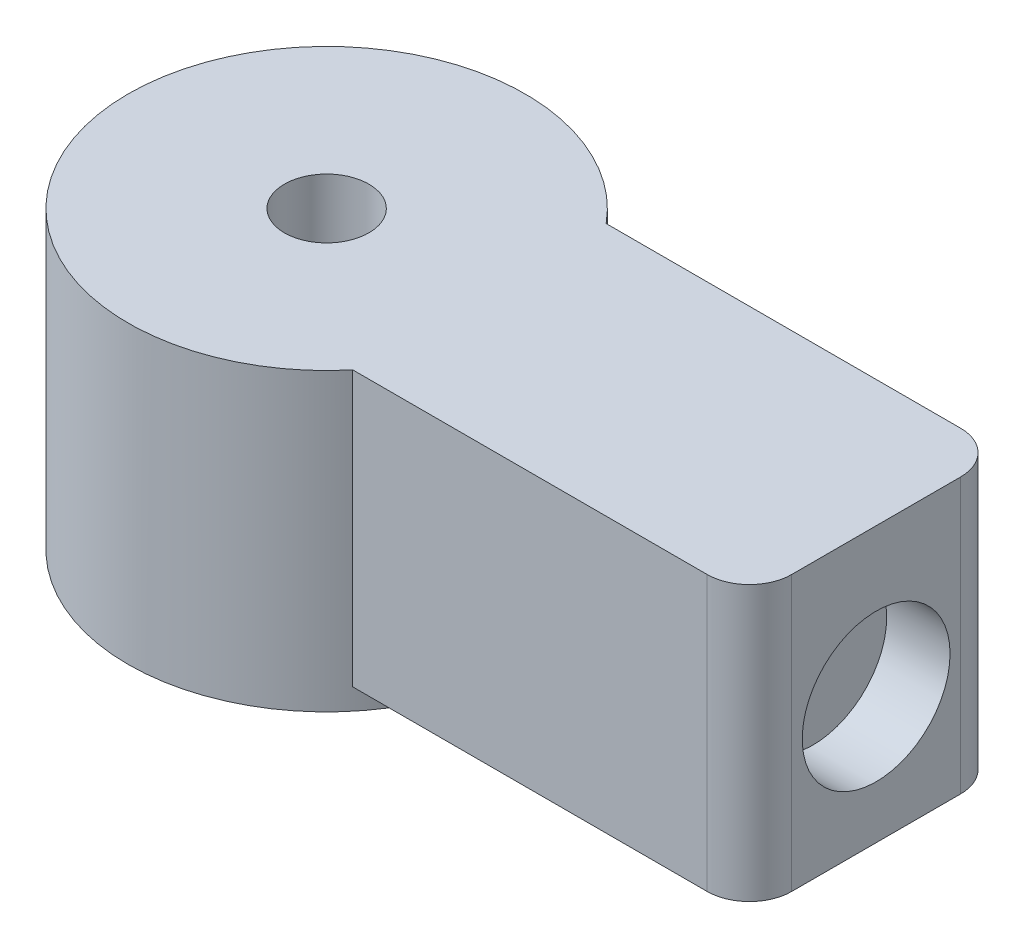
SolidWorks part; units mm, degrees
ref_plane "Front Plane" through (0, 0, 0) normal (0, 0, 1) x (1, 0, 0)
ref_plane "Top Plane" through (0, 0, 0) normal (0, 1, 0) x (1, 0, 0)
ref_plane "Right Plane" through (0, 0, 0) normal (1, 0, 0) x (0, 0, -1)
sketch "Sketch1" plane through (0, 0, 0) normal (0, 1, 0) x (1, 0, 0)
  circle A0 centre (0, 0) radius 2.5
  circle A1 centre (0, 0) radius 4.7
  dimension "D1" = 5
  dimension "D2" = 2.2
extrude "Boss-Extrude1" add sketch "Sketch1" along normal blind 2.5
sketch "Sketch2" plane through (0, 2.5, 0) normal (0, 1, 0) x (1, 0, 0)
  circle A0 centre (0, 0) radius 4.7
  circle A1 centre (0, 0) radius 4.7 construction
  dimension "D1" = 0
extrude "Boss-Extrude2" add sketch "Sketch2" along normal blind 4.5
sketch "Sketch3" plane through (0, 7, 0) normal (0, 1, 0) x (1, 0, 0)
  circle A0 centre (0, 0) radius 1
  dimension "D1" = 2
extrude "Cut-Extrude1" cut sketch "Sketch3" against normal blind 4.5
ref_plane "Plane1" through (4.7, 0, 0) normal (1, 0, 0) x (0, 0, -1)
sketch "Sketch6" plane through (4.7, 0, 0) normal (1, 0, 0) x (0, 0, -1)
  line L1 (3, 6.5) -> (-3, 6.5)
  line L2 (3, 6.5) -> (3, 0.5)
  line L3 (3, 0.5) -> (-3, 0.5)
  line L4 (-3, 6.5) -> (-3, 0.5)
  line L6 (-2.5, 0) -> (2.5, 0) construction
  line L7 (4.7, 7) -> (-4.7, 7) construction
  line L8 (4.7, 0) -> (4.7, 7) construction
  line L9 (-4.7, 7) -> (-4.7, 0) construction
  dimension "D1" = 6
  dimension "D2" = 6
  dimension "D3" = 1.7
  dimension "D4" = 1.7
  dimension "D5" = 0.5
  dimension "D6" = 0.5
extrude "Boss-Extrude3" add sketch "Sketch6" along normal blind 8.31 separate body
sketch "Sketch7" plane through (4.7, 0, 0) normal (-1, 0, 0) x (0, 0, 1)
  line L4 (-3, 6.5) -> (-3, 0.5)
  line L5 (-3, 0.5) -> (3, 0.5)
  line L6 (3, 0.5) -> (3, 6.5)
  line L7 (3, 6.5) -> (-3, 6.5)
  line L8 (-3, 6.5) -> (-3, 0.5)
  line L9 (-3, 0.5) -> (3, 0.5)
  line L10 (3, 0.5) -> (3, 6.5)
  line L11 (3, 6.5) -> (-3, 6.5)
  dimension "D1" = 0
extrude "Boss-Extrude4" add sketch "Sketch7" along normal blind 2
fillet "Fillet1" radius 1 2 edges at (13.01, 3.5, -3) (13.01, 3.5, 3)
sketch "Sketch8" plane through (13.01, 0, 0) normal (1, 0, 0) x (0, 0, -1)
  line L0 (-3, 6.5) -> (-3, 0.5) construction
  line L1 (3, 0.5) -> (3, 6.5) construction
  line L2 (2, 6.5) -> (-2, 6.5) construction
  line L3 (-2, 0.5) -> (2, 0.5) construction
  circle A0 centre (0, 3.5) radius 1.75
  dimension "D1" = 3.5
  dimension "D2" = 3
  dimension "D3" = 3
  dimension "D5" = 3
  dimension "D4" = 3
extrude "Cut-Extrude2" cut sketch "Sketch8" against normal blind 1.5
sketch "Sketch9" plane through (0, 6.5, 0) normal (0, 1, 0) x (1, 0, 0)
  line L3 (13.01, -2) -> (13.01, 2)
  line L4 (12.01, 3) -> (3.618, 3)
  line L5 (3.618, -3) -> (12.01, -3)
  line L6 (13.01, -2) -> (13.01, 2)
  line L7 (12.01, 3) -> (3.618, 3)
  line L8 (3.618, -3) -> (12.01, -3)
  arc A3 (13.01, 2) -> (12.01, 3) centre (12.01, 2) ccw
  arc A4 (3.618, -3) -> (3.618, 3) centre (0, 0) ccw
  arc A5 (12.01, -3) -> (13.01, -2) centre (12.01, -2) ccw
  arc A6 (13.01, 2) -> (12.01, 3) centre (12.01, 2) ccw
  arc A7 (3.618, -3) -> (3.618, 3) centre (0, 0) ccw
  arc A8 (12.01, -3) -> (13.01, -2) centre (12.01, -2) ccw
  dimension "D1" = 0
extrude "Boss-Extrude5" add sketch "Sketch9" along normal up to surface (0.5 mm away) up to face at (0, 7, 1)
